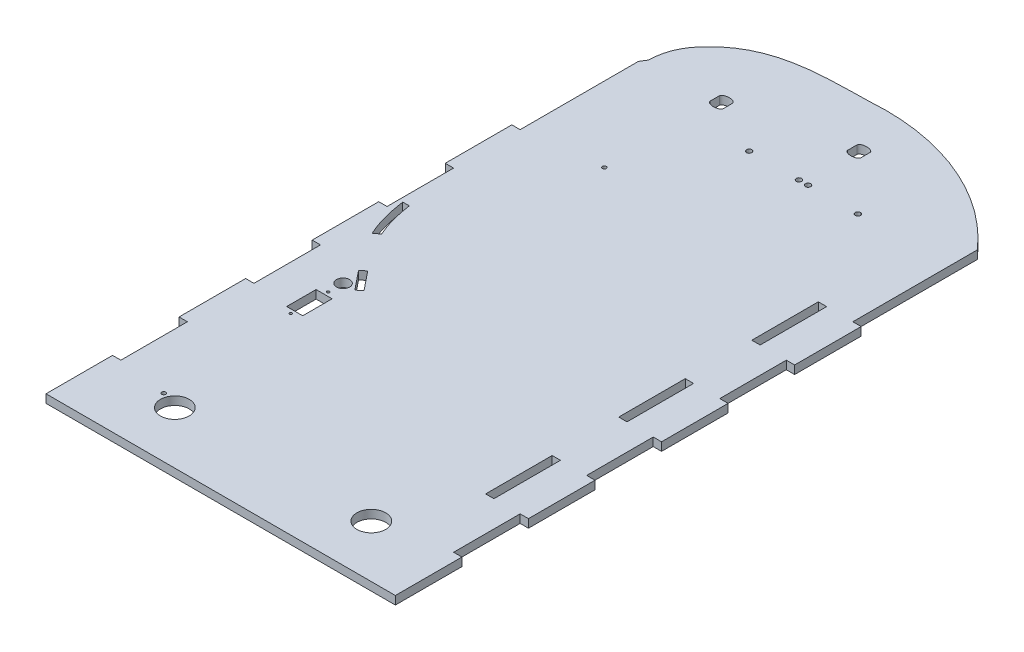
SolidWorks part; units mm, degrees
ref_plane "Front Plane" through (0, 0, 0) normal (0, 0, 1) x (1, 0, 0)
ref_plane "Top Plane" through (0, 0, 0) normal (0, 1, 0) x (1, 0, 0)
ref_plane "Right Plane" through (0, 0, 0) normal (1, 0, 0) x (0, 0, -1)
sketch "Sketch2" plane through (0, 0, 0) normal (0, 1, 0) x (1, 0, 0)
  line L0 (127, 0) -> (127, 40) construction
  line L1 (0, 0) -> (254, 0)
  line L2 (0, 0) -> (0, 508)
  line L3 (0, 508) -> (254, 508)
  line L4 (254, 0) -> (254, 508)
  line L5 (112, 0) -> (112, 40) construction
  line L6 (70.0293, 132.7246) -> (75.0014, 133.2514) construction
  line L8 (3.0464, 262.9295) -> (8.0974, 262.9295)
  line L9 (12.0177, 230.6311) -> (16.1196, 233.6878)
  line L10 (63.9635, 154.4733) -> (68.5195, 156.533) construction
  line L11 (31.3299, 200.9155) -> (35.2571, 204.0102)
  line L12 (42.9806, 186.4099) -> (46.8891, 189.5281)
  line L13 (27.8154, 172.0099) -> (40.0654, 172.0099)
  line L14 (27.8154, 172.0099) -> (27.8154, 149.5599)
  line L15 (40.0654, 172.0099) -> (40.0654, 149.5599)
  line L16 (27.8154, 149.5599) -> (40.0654, 149.5599)
  line L17 (0, 367.5) -> (57.0911, 367.5) construction
  line L20 (0, 358) -> (57.4432, 358) construction
  line L21 (57.0911, 367.5) -> (57.0911, 358) construction
  line L22 (138.65, 474.05) -> (138.65, 467.05) construction
  line L23 (148.65, 467.05) -> (148.65, 474.05) construction
  line L24 (138.65, 474.05) -> (138.65, 467.05)
  line L25 (148.65, 467.05) -> (148.65, 474.05)
  line L26 (63.65, 447.05) -> (63.65, 454.05) construction
  line L27 (53.65, 454.05) -> (53.65, 447.05) construction
  line L28 (63.65, 447.05) -> (63.65, 454.05)
  line L29 (53.65, 454.05) -> (53.65, 447.05)
  circle A0 centre (52, 40) radius 11
  circle A1 centre (202, 40) radius 11
  circle A2 centre (38.2469, 45.3329) radius 1.5
  circle A3 centre (34.0154, 186.4099) radius 5
  arc A4 (33.4154, 175.7599) -> (34.6154, 175.7599) centre (34.0154, 174.9599) ccw construction
  arc A5 (33.4154, 175.7599) -> (34.6154, 175.7599) centre (34.0154, 174.9599) ccw
  arc A6 (34.6154, 175.7599) -> (33.4154, 175.7599) centre (34.0154, 174.9599) ccw
  arc A7 (34.6154, 145.6599) -> (33.4154, 145.6599) centre (34.0154, 146.4599) ccw construction
  arc A8 (34.6154, 145.6599) -> (33.4154, 145.6599) centre (34.0154, 146.4599) ccw
  arc A9 (34.6154, 145.6599) -> (33.4154, 145.6599) centre (34.0154, 146.4599) cw
  circle A10 centre (57.0911, 362.75) radius 1.5
  circle A11 centre (184.6289, 428.7954) radius 2 construction
  circle A12 centre (146.6289, 428.7954) radius 2 construction
  circle A13 centre (139.6289, 428.7954) radius 2 construction
  circle A14 centre (101.6289, 428.7954) radius 2 construction
  circle A15 centre (184.6289, 428.7954) radius 2
  circle A16 centre (146.6289, 428.7954) radius 2
  circle A17 centre (139.6289, 428.7954) radius 2
  circle A18 centre (101.6289, 428.7954) radius 2
  ellipse E0 centre (143.65, 474.05) end of major axis (138.65, 474.05) minor radius 2.5 (148.65, 474.05) -> (138.65, 474.05) ccw construction
  ellipse E1 centre (143.65, 467.05) end of major axis (138.65, 467.05) minor radius 2.5 (138.65, 467.05) -> (148.65, 467.05) ccw construction
  ellipse E2 centre (143.65, 467.05) end of major axis (138.65, 467.05) minor radius 2.5 (138.65, 467.05) -> (148.65, 467.05) ccw
  ellipse E3 centre (143.65, 474.05) end of major axis (138.65, 474.05) minor radius 2.5 (148.65, 474.05) -> (138.65, 474.05) ccw
  ellipse E4 centre (58.65, 447.05) end of major axis (63.65, 447.05) minor radius 2.5 (53.65, 447.05) -> (63.65, 447.05) ccw construction
  ellipse E5 centre (58.65, 454.05) end of major axis (63.65, 454.05) minor radius 2.5 (63.65, 454.05) -> (53.65, 454.05) ccw construction
  ellipse E6 centre (58.65, 447.05) end of major axis (63.65, 447.05) minor radius 2.5 (53.65, 447.05) -> (63.65, 447.05) ccw
  ellipse E7 centre (58.65, 454.05) end of major axis (63.65, 454.05) minor radius 2.5 (63.65, 454.05) -> (53.65, 454.05) ccw
  spline S0 degree 3 poles (0, 358) (10.2414, 318.2744) (-10.3205, 225.9555) (70.6512, 174.3118) (75.0014, 133.2514) knots 0 0 0 0 0.517006 1 1 1 1 construction
  spline S1 degree 3 poles (57.0275, 368.1055) (60.011, 340.8516) (38.8621, 298.2828) (61.0822, 235.4033) (84.5865, 206.7018) (104.9746, 198.8412) knots 0 0 0 0 0.426438 0.676001 1 1 1 1 construction
  spline S2 degree 1 poles (-4.8417, 356.7518) (70.0293, 132.7246) knots 0 0 1 1 construction
  spline S3 degree 3 poles (-4.8417, 356.7518) (-4.2453, 354.4384) (-3.2098, 349.8001) (-1.6146, 340.1963) (-0.4104, 327.7832) (0.2492, 312.4005) (0.7261, 291.8409) (1.4026, 275.812) (2.8811, 264.0829) (3.206, 261.7747) (3.5674, 259.4757) (3.9542, 257.1833) (4.5302, 254.1018) (5.5014, 249.6086) (6.6895, 245.0428) (8.2086, 240.135) (9.6429, 236.1559) (11.2633, 232.2426) (12.5555, 229.4544) (14.3601, 225.8497) (18.1885, 218.946) (23.3984, 211.2859) (29.2816, 203.4962) (32.93, 198.8824) (36.8298, 194.0373) (40.7355, 189.2215) (46.6866, 181.7864) (53.9965, 172.1125) (59.9683, 162.643) (63.1245, 156.3309) (64.1438, 154.0765) (64.4933, 153.279) (64.8362, 152.4792) (65.7137, 150.3629) (66.7102, 147.6655) (67.6191, 144.7625) (68.2641, 142.4625) (68.8611, 140.0122) (69.3531, 137.5307) (69.7433, 135.1238) (69.9343, 133.621) (70.0293, 132.7246) knots 0 0 0 0 0.03125 0.0625 0.125 0.1875 0.25 0.371368 0.378402 0.392471 0.399505 0.406539 0.420608 0.4375 0.462351 0.477976 0.5 0.513677 0.529302 0.537114 0.5625 0.625 0.649179 0.680429 0.696054 0.724459 0.755709 0.8125 0.875 0.898852 0.904562 0.907417 0.910272 0.915981 0.9375 0.948072 0.955885 0.96875 0.980913 0.988548 1 1 1 1 only from (0, 317.7537) to (70.0293, 132.7246) construction
  spline S4 degree 1 poles (35.2571, 204.0102) (46.8891, 189.5281) knots 0 0 1 1
  spline S5 degree 1 poles (31.3299, 200.9155) (42.9806, 186.4099) knots 0 0 1 1
  spline S6 degree 3 poles (3.0464, 262.9295) (4.6075, 251.8412) (7.2857, 240.8284) (12.0177, 230.6311) knots 0 0 0 0 1 1 1 1
  spline S7 degree 3 poles (8.0974, 262.9295) (9.5523, 252.911) (11.965, 242.952) (16.1196, 233.6878) knots 0 0 0 0 1 1 1 1
  spline S8 degree 3 poles (68.5195, 156.533) (70.3934, 152.3928) (73.1628, 144.7538) (74.6292, 136.7727) (75.0014, 133.2514) knots 0 0 0 0 0.562151 1 1 1 1 construction
  spline S9 degree 3 poles (63.9635, 154.4733) (65.5406, 150.9864) (68.1883, 143.8779) (69.6381, 136.4314) (70.0293, 132.7246) knots 0 0 0 0 0.506681 1 1 1 1 construction
  point P86 (138.65, 470.55)
  dimension "D3" = 22
  dimension "D9" = 3
  dimension "D10" = 3
  dimension "D1" = 508
  dimension "D2" = 254
  dimension "D4" = 40
  dimension "D5" = 15
  dimension "D6" = 60
  dimension "D7" = 150
  dimension "D8" = 5
extrude "Boss-Extrude1" add sketch "Sketch2" along normal blind 6.35
sketch "Sketch3" plane through (0, 6.35, 0) normal (0, 1, 0) x (1, 0, 0)
  line L0 (127, 508) -> (127, 338.6667) construction
  line L1 (254, 508) -> (0, 508) construction
  line L2 (127, 338.6667) -> (127, 169.3333) construction
  line L3 (127, 169.3333) -> (127, 0) construction
  line L4 (0, 0) -> (254, 0) construction
  line L5 (254, 0) -> (254, 508) construction
  line L6 (254, 508) -> (127, 508)
  line L7 (254, 450.6701) -> (254, 508)
  arc A1 (127, 508) -> (254, 450.6701) centre (127, 338.6667) cw
extrude "Cut-Extrude1" cut sketch "Sketch3" against normal up to next
sketch "Sketch5" plane through (0, 6.35, 0) normal (0, 1, 0) x (1, 0, 0)
  line L0 (254, 450.6701) -> (0, 450.6701) construction
  line L1 (0, 508) -> (0, 0) construction
  line L2 (3, 450.6701) -> (0, 445.8071)
  line L3 (0, 508) -> (0, 445.8071)
  line L6 (0, 508) -> (0, 526.7662)
  line L7 (0, 526.7662) -> (127, 526.7662)
  line L8 (127, 508) -> (127, 526.7662)
  circle A0 centre (45, 450.6701) radius 22 construction
  arc A2 (16.9934, 481.9692) -> (3, 450.6701) centre (45, 450.6701) ccw
  circle A3 centre (45, 450.6701) radius 42 construction
  spline S0 degree 3 poles (16.9934, 481.9692) (44.7711, 511.7661) (91.2093, 505.8566) (127, 508) knots 0 0 0 0 1 1 1 1
  dimension "D1" = 44
  dimension "D3" = 45
  dimension "D2" = 20
extrude "Cut-Extrude2" cut sketch "Sketch5" against normal up to next
sketch "Sketch7" plane through (0, 0, 0) normal (0, -1, 0) x (1, 0, 0)
  line L1 (254, 0) -> (260.35, 0)
  line L2 (254, 0) -> (254, -50.8)
  line L3 (254, -50.8) -> (260.35, -50.8)
  line L4 (260.35, 0) -> (260.35, -50.8)
  line L5 (0, 0) -> (-6.35, 0)
  line L6 (0, 0) -> (0, -50.8)
  line L7 (0, -50.8) -> (-6.35, -50.8)
  line L8 (-6.35, 0) -> (-6.35, -50.8)
  dimension "D1" = 6.35
  dimension "D2" = 50.8
  dimension "D3" = 6.35
  dimension "D4" = 50.8
extrude "Boss-Extrude2" add sketch "Sketch7" against normal up to surface (6.35 mm away) up to face at (143.65, 6.35, -470.55)
pattern_linear "LPattern1" count 4 spacing 101.6 along (0, 0, -1) of "Boss-Extrude2"
sketch "Sketch8" plane through (0, 6.35, 0) normal (0, 1, 0) x (1, 0, 0)
  line L0 (254, 152.4) -> (254, 203.2) construction
  line L5 (234, 152.4) -> (227.65, 152.4)
  line L7 (234, 152.4) -> (234, 101.6)
  line L9 (234, 101.6) -> (227.65, 101.6)
  line L10 (227.65, 152.4) -> (227.65, 101.6)
  line L11 (254, 101.6) -> (260.35, 101.6) construction
  line L12 (260.35, 101.6) -> (260.35, 152.4) construction
  dimension "D1" = 20
extrude "Cut-Extrude3" cut sketch "Sketch8" against normal up to next
pattern_linear "LPattern2" count 3 spacing 101.6 along (0, 0, -1) of "Cut-Extrude3"
sketch "Slider" plane through (0, 6.35, 6.35) normal (0, 1, 0) x (1, 0, 0)
  line L0 (0, 452.1571) -> (0, 361.95) construction
  line L6 (54.1176, 177.8402) -> (58.2442, 180.6634) construction
  spline S0 degree 3 poles (0, 364.2407) (10.0932, 324.5031) (-6.7408, 249.3382) (44.5453, 200.6868) (58.2442, 180.6634) knots 0 0 0 0 0.63201 1 1 1 1 construction
  spline S1 degree 3 poles (57.0275, 368.1055) (60.011, 340.8516) (38.8621, 298.2828) (61.0822, 235.4033) (84.5865, 206.7018) (104.9746, 198.8412) knots 0 0 0 0 0.426438 0.676001 1 1 1 1 construction
  spline S2 degree 1 poles (-4.8461, 363.0098) (54.1176, 177.8402) knots 0 0 1 1 construction
  spline S3 degree 3 poles (-4.8461, 363.0098) (-4.3659, 361.1191) (-3.5097, 357.3301) (-2.1229, 349.5349) (-0.9477, 339.5089) (-0.1716, 327.1083) (0.3662, 310.2426) (0.7835, 288.8153) (2.7416, 267.6076) (6.4419, 251.188) (10.6067, 239.2328) (16.4686, 227.9252) (23.4848, 217.3517) (31.2063, 207.235) (39.1962, 197.3973) (45.7189, 189.2885) (50.658, 182.7615) (52.9812, 179.5011) (54.1176, 177.8402) knots 0 0 0 0 0.03125 0.0625 0.125 0.1875 0.25 0.375 0.5 0.5625 0.625 0.6875 0.75 0.8125 0.875 0.9375 0.96875 1 1 1 1 only from (0, 321.3493) to (54.1176, 177.8402) construction
  dimension "D8" = 5
